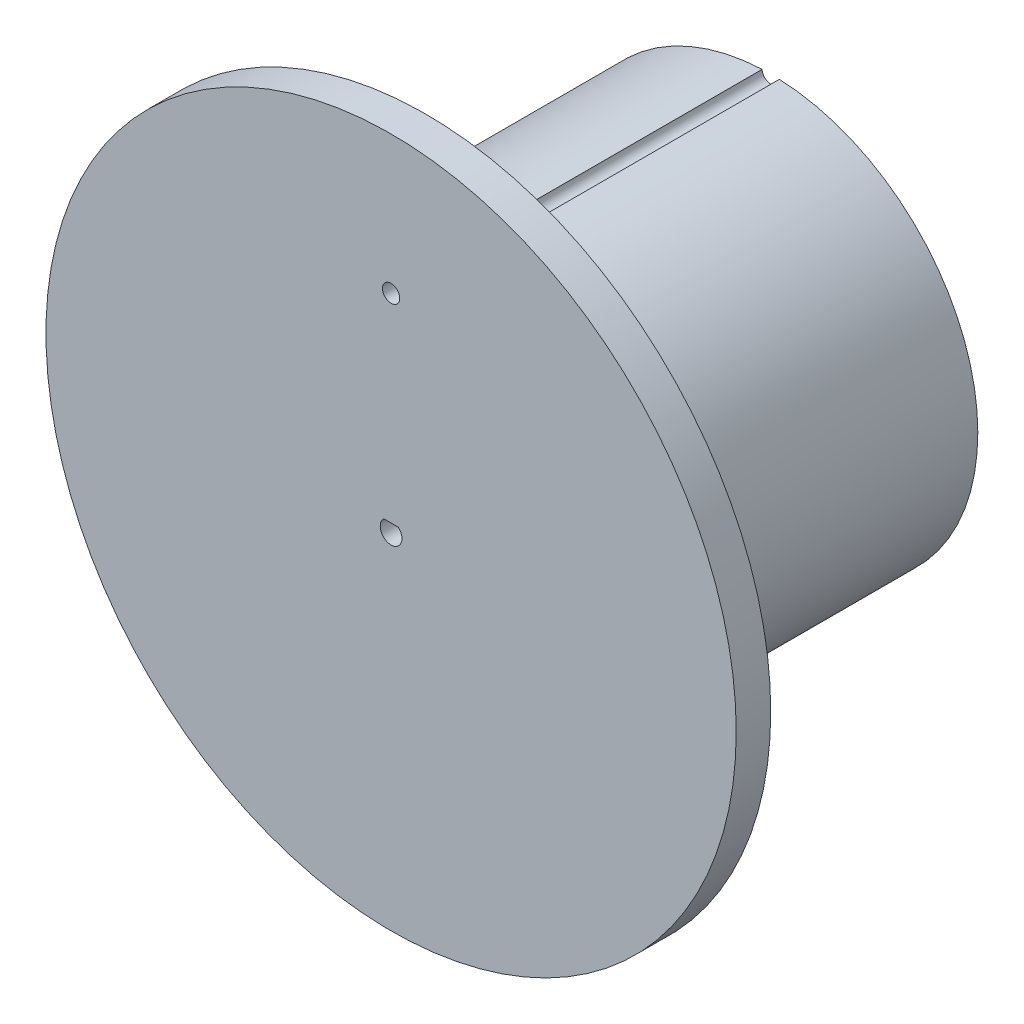
SolidWorks part; units mm, degrees
ref_plane "Front Plane" through (0, 0, 0) normal (0, 0, 1) x (1, 0, 0)
ref_plane "Top Plane" through (0, 0, 0) normal (0, 1, 0) x (1, 0, 0)
ref_plane "Right Plane" through (0, 0, 0) normal (1, 0, 0) x (0, 0, -1)
sketch "Sketch2" plane through (0, 0, 0) normal (0, 0, 1) x (1, 0, 0)
  circle A0 centre (0, 0) radius 38.1
  dimension "D1" = 76.2
extrude "Boss-Extrude1" add sketch "Sketch2" along normal mid plane 63.5
sketch "Sketch5" plane through (0, 0, 31.75) normal (0, 0, 1) x (1, 0, 0)
  circle A0 centre (0, 0) radius 63.5
  dimension "D1" = 127
extrude "Boss-Extrude2" add sketch "Sketch5" along normal blind 6.35
sketch "Sketch7" plane through (0, 0, 31.75) normal (0, 0, -1) x (-1, 0, 0)
  line L0 (0, 0) -> (0, 54.1635) construction
  circle A0 centre (0, 38.1) radius 1.5875
  circle A1 centre (0, 0) radius 38.1 construction
  dimension "D1" = 3.175
extrude "Cut-Extrude1" cut sketch "Sketch7" against normal through all both and the other way through all
sketch "Sketch8" plane through (0, 0, -31.75) normal (0, 0, -1) x (-1, 0, 0)
  line L0 (-1.3229, 1.5) -> (1.3229, 1.5)
  line L1 (0, -2) -> (4.1971, -2) construction
  arc A0 (-1.3229, 1.5) -> (1.3229, 1.5) centre (0, 0) ccw
  point P6 (0, 1.5)
  dimension "D1" = 4
  dimension "D2" = 3.5
extrude "Cut-Extrude2" cut sketch "Sketch8" against normal through all
sketch "Sketch9" plane through (0, 0, -31.75) normal (0, 0, -1) x (-1, 0, 0)
  line L0 (0, 0) -> (0, 19.05) construction
  circle A0 centre (0, 19.05) radius 4.7625
  dimension "D2" = 9.525
  dimension "D1" = 19.05
extrude "Cut-Extrude3" cut sketch "Sketch9" against normal blind 19.05
chamfer "Chamfer1" distance 3.175 angle 45 1 edges at (-4.7625, 19.05, -31.75)
mirror "Mirror1" about plane through (0, 0, 0) normal (0, 1, 0) of "Chamfer1", "Cut-Extrude3"
